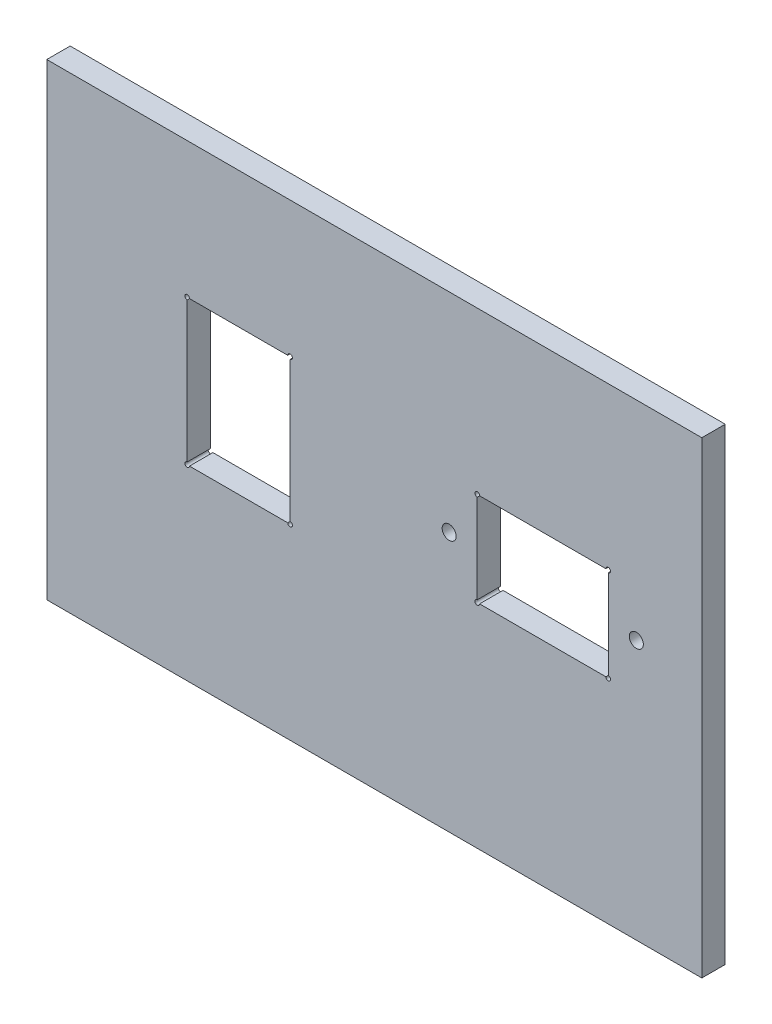
SolidWorks part; units mm, degrees
material "Perspex (TM) GS Acrylic Cast Sheet"
ref_plane "Ebene vorne" through (0, 0, 0) normal (0, 0, 1) x (1, 0, 0)
ref_plane "Ebene oben" through (0, 0, 0) normal (0, 1, 0) x (1, 0, 0)
ref_plane "Ebene rechts" through (0, 0, 0) normal (1, 0, 0) x (0, 0, -1)
sketch "Skizze1" plane through (0, 0, 0) normal (0, 0, 1) x (1, 0, 0)
  line L1 (-70, 50) -> (70, 50)
  line L2 (-70, 50) -> (-70, -50)
  line L3 (-70, -50) -> (70, -50)
  line L4 (70, 50) -> (70, -50)
  line L5 (-70, 50) -> (70, -50) construction
  line L6 (-70, -50) -> (70, 50) construction
  point P0 (0, 0)
  dimension "D1" = 140
  dimension "D2" = 100
extrude "Aufsatz-Linear austragen1" add sketch "Skizze1" along normal blind 5
sketch "Skizze2" plane through (0, 0, 5) normal (0, 0, 1) x (1, 0, 0)
  line L0 (-70, 50) -> (-70, -50) construction
  line L1 (-40, 21) -> (-18, 21)
  line L2 (-40, 21) -> (-40, -10)
  line L3 (-40, -10) -> (-18, -10)
  line L4 (-18, 21) -> (-18, -10)
  line L5 (-40, 21) -> (-18, -10) construction
  line L6 (-40, -10) -> (-18, 21) construction
  line L7 (-70, -50) -> (70, -50) construction
  dimension "D1" = 22
  dimension "D2" = 31
  dimension "D3" = 30
  dimension "D4" = 40
extrude "Schnitt-Linear austragen1" cut sketch "Skizze2" against normal through all
sketch "Skizze4" plane through (0, 0, 5) normal (0, 0, 1) x (1, 0, 0)
  line L0 (70, -50) -> (70, 50) construction
  line L1 (22, 15.5) -> (50, 15.5)
  line L2 (22, 15.5) -> (22, -4.5)
  line L3 (22, -4.5) -> (50, -4.5)
  line L4 (50, 15.5) -> (50, -4.5)
  line L5 (22, 15.5) -> (50, -4.5) construction
  line L6 (22, -4.5) -> (50, 15.5) construction
  line L7 (36, 5.5) -> (-18, 5.5) construction
  line L8 (-18, -10) -> (-18, 21) construction
  line L9 (56, 5.5) -> (16, 5.5) construction
  circle A0 centre (16, 5.5) radius 1.5
  circle A1 centre (56, 5.5) radius 1.5
  point P0 (36, 5.5)
  point P14 (36, 5.5)
  dimension "D4" = 3
  dimension "D1" = 28
  dimension "D2" = 20
  dimension "D3" = 20
  dimension "D5" = 40
extrude "Schnitt-Linear austragen3" cut sketch "Skizze4" against normal through all
sketch "Skizze3" plane through (0, 0, 5) normal (0, 0, 1) x (1, 0, 0)
  circle A0 centre (-40, 21) radius 0.5
  circle A1 centre (-18, 21) radius 0.5
  circle A2 centre (-18, -10) radius 0.5
  circle A3 centre (-40, -10) radius 0.5
  circle A4 centre (22, 15.5) radius 0.5
  circle A5 centre (50, 15.5) radius 0.5
  circle A6 centre (50, -4.5) radius 0.5
  circle A7 centre (22, -4.5) radius 0.5
  dimension "D1" = 1
extrude "Schnitt-Linear austragen2" cut sketch "Skizze3" against normal through all
